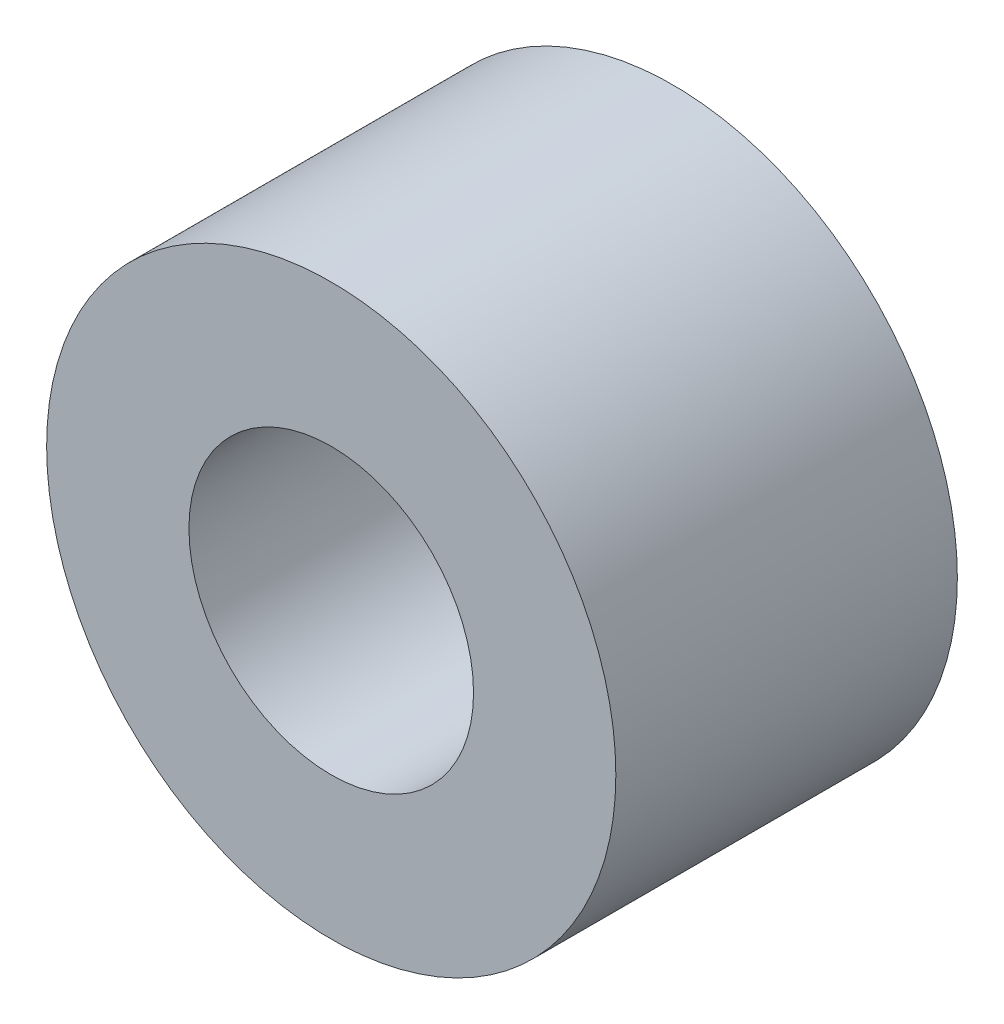
SolidWorks part; units mm, degrees
ref_plane "Płaszczyzna przednia" through (0, 0, 0) normal (0, 0, 1) x (1, 0, 0)
ref_plane "Płaszczyzna górna" through (0, 0, 0) normal (0, 1, 0) x (1, 0, 0)
ref_plane "Płaszczyzna prawa" through (0, 0, 0) normal (1, 0, 0) x (0, 0, -1)
sketch "Szkic1" plane through (0, 0, 0) normal (0, 0, 1) x (1, 0, 0)
  circle A0 centre (0, 0) radius 5
  circle A1 centre (0, 0) radius 2.5
  dimension "D1" = 10
  dimension "D2" = 5
extrude "Dodanie-wyciągnięcie1" add sketch "Szkic1" along normal blind 6
